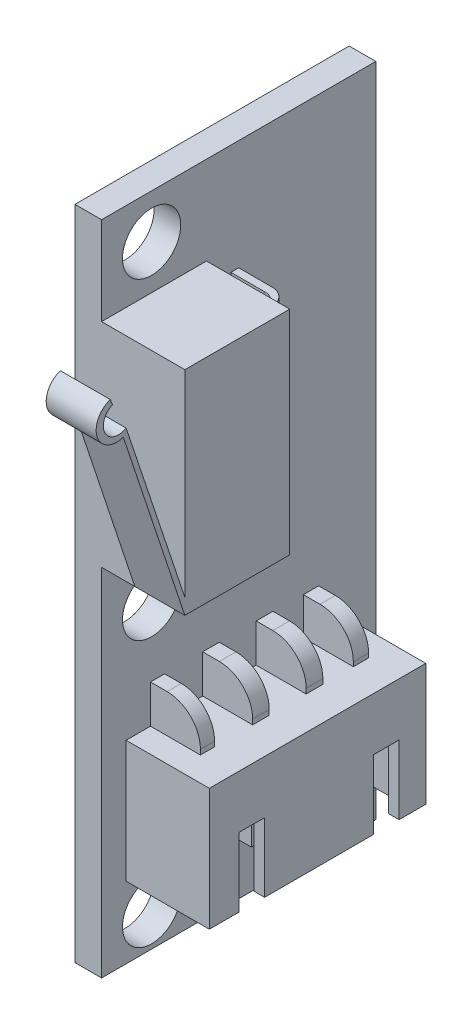
SolidWorks part; units mm, degrees
other "Camera1"
ref_plane "Front Plane" through (0, 0, 0) normal (0, 0, 1) x (1, 0, 0)
ref_plane "Top Plane" through (0, 0, 0) normal (0, 1, 0) x (1, 0, 0)
ref_plane "Right Plane" through (0, 0, 0) normal (1, 0, 0) x (0, 0, -1)
sketch "Sketch1" plane through (0, 0, 0) normal (1, 0, 0) x (0, 0, -1)
  line L1 (-8.235, 19.72) -> (8.235, 19.72)
  line L2 (-8.235, 19.72) -> (-8.235, -19.72)
  line L3 (-8.235, -19.72) -> (8.235, -19.72)
  line L4 (8.235, 19.72) -> (8.235, -19.72)
  line L5 (-8.235, 19.72) -> (8.235, -19.72) construction
  line L6 (-8.235, -19.72) -> (8.235, 19.72) construction
  point P0 (0, 0)
  dimension "D1" = 16.47
  dimension "D2" = 39.44
extrude "Boss-Extrude1" add sketch "Sketch1" along normal blind 1.6
sketch "Sketch2" plane through (1.6, 0, 0) normal (1, 0, 0) x (0, 0, -1)
  line L0 (-8.235, 19.72) -> (-8.235, -19.72) construction
  line L1 (-8.235, 14.42) -> (-1.935, 14.42)
  line L2 (-8.235, 14.42) -> (-8.235, 1.64)
  line L3 (-8.235, 1.64) -> (-1.935, 1.64)
  line L4 (-1.935, 14.42) -> (-1.935, 1.64)
  line L5 (8.235, 19.72) -> (-8.235, 19.72) construction
  dimension "D1" = 6.3
  dimension "D2" = 12.78
  dimension "D3" = 5.3
extrude "Boss-Extrude2" add sketch "Sketch2" along normal blind 5
sketch "Sketch3" plane through (1.6, 0, 0) normal (1, 0, 0) x (0, 0, -1)
  line L0 (8.235, -19.72) -> (8.235, 19.72) construction
  line L1 (-6.765, -8.09) -> (6.235, -8.09)
  line L2 (-6.765, -8.09) -> (-6.765, -15.42)
  line L3 (-6.765, -15.42) -> (6.235, -15.42)
  line L4 (6.235, -8.09) -> (6.235, -15.42)
  line L5 (-8.235, -19.72) -> (8.235, -19.72) construction
  dimension "D1" = 13
  dimension "D2" = 7.33
  dimension "D3" = 2
  dimension "D4" = 4.3
extrude "Boss-Extrude3" add sketch "Sketch3" along normal blind 5
sketch "Sketch4" plane through (1.6, 0, 0) normal (1, 0, 0) x (0, 0, -1)
  line L0 (6.235, -8.09) -> (-6.765, -8.09) construction
  line L1 (-5.2994, -8.09) -> (-4.4502, -8.09)
  line L2 (-5.2994, -8.09) -> (-5.2994, -5.7907)
  line L3 (-5.2994, -5.7907) -> (-4.4502, -5.7907)
  line L4 (-4.4502, -8.09) -> (-4.4502, -5.7907)
  line L5 (6.235, -8.09) -> (-6.765, -8.09) construction
  line L6 (-1.1671, -5.7907) -> (-2.1638, -5.7907)
  line L7 (-1.1671, -5.7907) -> (-1.1671, -8.09)
  line L8 (-1.1671, -8.09) -> (-2.1638, -8.09)
  line L9 (-2.1638, -5.7907) -> (-2.1638, -8.09)
  line L11 (2.0534, -5.7907) -> (1.0488, -5.7907)
  line L12 (2.0534, -5.7907) -> (2.0534, -8.09)
  line L13 (2.0534, -8.09) -> (1.0488, -8.09)
  line L14 (1.0488, -5.7907) -> (1.0488, -8.09)
  line L15 (4.8012, -5.841) -> (3.8853, -5.841)
  line L16 (4.8012, -5.841) -> (4.8012, -8.09)
  line L17 (4.8012, -8.09) -> (3.8853, -8.09)
  line L18 (3.8853, -5.841) -> (3.8853, -8.09)
extrude "Boss-Extrude4" add sketch "Sketch4" along normal blind 3
sketch "Sketch5" plane through (0, -15.42, 0) normal (0, -1, 0) x (-1, 0, 0)
  line L1 (-2.2221, -6.0977) -> (-5.9779, -6.0977)
  line L2 (-2.2221, -6.0977) -> (-2.2221, 5.5677)
  line L3 (-2.2221, 5.5677) -> (-5.9779, 5.5677)
  line L4 (-5.9779, -6.0977) -> (-5.9779, 5.5677)
  line L5 (-2.2221, -6.0977) -> (-5.9779, 5.5677) construction
  line L6 (-2.2221, 5.5677) -> (-5.9779, -6.0977) construction
  point P0 (-4.1, -0.265)
extrude "Cut-Extrude1" cut sketch "Sketch5" against normal blind 6
fillet "Fillet2" radius 2 4 edges at (4.6, -5.841, -4.3433) (4.6, -5.7907, -1.5511) (4.6, -5.7907, 1.6655) (4.6, -5.7907, 4.8748)
sketch "Sketch6" plane through (0, -9.42, 0) normal (0, -1, 0) x (-1, 0, 0)
  line L1 (-4.5968, -4.6386) -> (-3.5718, -4.6386)
  line L2 (-4.5968, -4.6386) -> (-4.5968, -3.5291)
  line L3 (-4.5968, -3.5291) -> (-3.5718, -3.5291)
  line L4 (-3.5718, -4.6386) -> (-3.5718, -3.5291)
  line L5 (-4.5968, -4.6386) -> (-3.5718, -3.5291) construction
  line L6 (-4.5968, -3.5291) -> (-3.5718, -4.6386) construction
  line L7 (-4.5968, -2.2292) -> (-3.5718, -2.2292)
  line L8 (-4.5968, -2.2292) -> (-4.5968, -1.2026)
  line L9 (-4.5968, -1.2026) -> (-3.5718, -1.2026)
  line L10 (-3.5718, -2.2292) -> (-3.5718, -1.2026)
  line L11 (-4.5968, -2.2292) -> (-3.5718, -1.2026) construction
  line L12 (-4.5968, -1.2026) -> (-3.5718, -2.2292) construction
  line L13 (-4.6125, 0.6189) -> (-3.5875, 0.6189)
  line L14 (-4.6125, 0.6189) -> (-4.6125, 1.6787)
  line L15 (-4.6125, 1.6787) -> (-3.5875, 1.6787)
  line L16 (-3.5875, 0.6189) -> (-3.5875, 1.6787)
  line L17 (-4.6125, 0.6189) -> (-3.5875, 1.6787) construction
  line L18 (-4.6125, 1.6787) -> (-3.5875, 0.6189) construction
  line L19 (-4.6125, 2.9206) -> (-3.5875, 2.9206)
  line L20 (-4.6125, 2.9206) -> (-4.6125, 4.0135)
  line L21 (-4.6125, 4.0135) -> (-3.5875, 4.0135)
  line L22 (-3.5875, 2.9206) -> (-3.5875, 4.0135)
  line L23 (-4.6125, 2.9206) -> (-3.5875, 4.0135) construction
  line L24 (-4.6125, 4.0135) -> (-3.5875, 2.9206) construction
  point P0 (-4.0843, -4.0839)
  point P5 (-4.0843, -1.7159)
  point P10 (-4.1, 1.1488)
  point P15 (-4.1, 3.467)
extrude "Boss-Extrude5" add sketch "Sketch6" along normal blind 5
sketch "Sketch7" plane through (6.6, 0, 0) normal (1, 0, 0) x (0, 0, -1)
  line L0 (-6.765, -15.42) -> (6.235, -15.42) construction
  line L1 (-4.9695, -15.42) -> (-3.4449, -15.42)
  line L2 (-4.9695, -15.42) -> (-4.9695, -11.2731)
  line L3 (-4.9695, -11.2731) -> (-3.4449, -11.2731)
  line L4 (-3.4449, -15.42) -> (-3.4449, -11.2731)
  line L6 (3.1065, -11.2731) -> (4.6311, -11.2731)
  line L7 (3.1065, -11.2731) -> (3.1065, -15.42)
  line L8 (3.1065, -15.42) -> (4.6311, -15.42)
  line L9 (4.6311, -11.2731) -> (4.6311, -15.42)
extrude "Cut-Extrude2" cut sketch "Sketch7" against normal blind 1
sketch "Sketch8" plane through (1.6, 0, 0) normal (1, 0, 0) x (0, 0, -1)
  line L0 (-1.935, 1.64) -> (-1.935, 14.42) construction
  line L1 (-1.935, 13.1007) -> (0, 13.1007)
  line L2 (-1.935, 13.1007) -> (-1.935, 12.1681)
  line L3 (-1.935, 12.1681) -> (0, 12.1681)
  line L4 (0, 13.1007) -> (0, 12.1681)
  line L5 (-1.935, 1.64) -> (-1.935, 14.42) construction
  line L6 (-1.935, 8.3565) -> (0, 8.3565)
  line L7 (-1.935, 8.3565) -> (-1.935, 7.4645)
  line L8 (-1.935, 7.4645) -> (0, 7.4645)
  line L9 (0, 8.3565) -> (0, 7.4645)
  line L11 (-1.935, 3.288) -> (0, 3.288)
  line L12 (-1.935, 3.288) -> (-1.935, 2.477)
  line L13 (-1.935, 2.477) -> (0, 2.477)
  line L14 (0, 3.288) -> (0, 2.477)
extrude "Boss-Extrude6" add sketch "Sketch8" along normal blind 3
fillet "Fillet3" radius 1 3 edges at (4.6, 12.6344, 0) (4.6, 7.9105, 0) (4.6, 2.8825, 0)
sketch "Sketch9" plane through (0, 13.1007, 0) normal (0, 1, 0) x (1, 0, 0)
  line L0 (1.6, -0.4698) -> (3.5971, -0.4698)
  line L1 (1.6, 8.235) -> (1.6, -8.235) construction
  line L2 (4.2436, -1.0107) -> (4.2436, -1.935)
  line L3 (6.6, -1.935) -> (1.6, -1.935) construction
  line L4 (4.2436, -1.935) -> (1.6, -1.935)
  line L5 (1.6, -1.935) -> (1.6, -0.4698)
  spline S0 degree 3 poles (3.5971, -0.4698) (4.1488, -0.431) (4.233, -0.7925) (4.2436, -1.0107) knots 0 0 0 0 1 1 1 1
extrude "Cut-Extrude3" cut sketch "Sketch9" against normal blind 11
sketch "Sketch10" plane through (1.6, 0, 0) normal (1, 0, 0) x (0, 0, -1)
  circle A0 centre (-5.2326, -1.7238) radius 1.75
  circle A1 centre (-5.2326, 17.0729) radius 1.75
  circle A2 centre (-5.2326, -17.6943) radius 1.75
  circle A3 centre (4.9362, -17.6943) radius 1.75
  dimension "D1" = 3.5
extrude "Cut-Extrude4" cut sketch "Sketch10" against normal blind 11
sketch "Sketch11" plane through (6.6, 0, 0) normal (1, 0, 0) x (0, 0, -1)
  line L0 (-8.235, 1.64) -> (-11.9304, 12.7539)
  line L1 (-8.235, 2.5833) -> (-11.762, 13.1469)
  line L2 (-8.235, 14.42) -> (-8.235, 1.64) construction
  line L3 (-12.7128, 15.107) -> (-12.5826, 14.7711)
  line L4 (-8.235, 2.5833) -> (-8.235, 1.64)
  arc A0 (-12.7128, 15.107) -> (-11.9304, 12.7539) centre (-12.3216, 13.9305) ccw
  arc A1 (-12.5826, 14.7711) -> (-11.762, 13.1469) centre (-12.2199, 13.9349) ccw
extrude "Boss-Extrude7" add sketch "Sketch11" against normal blind 3
